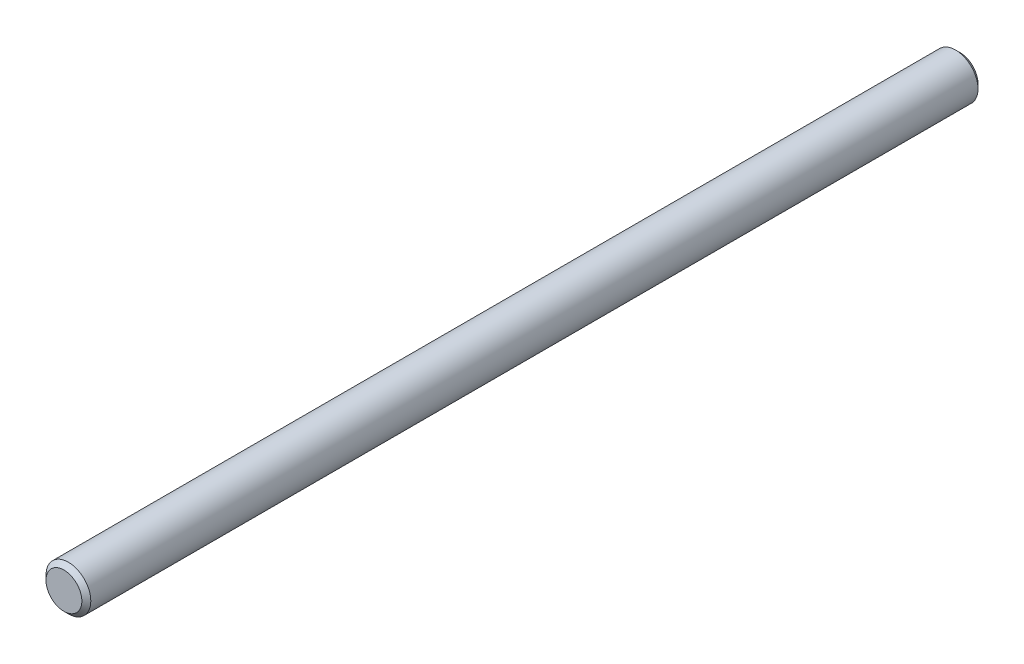
SolidWorks part; units mm, degrees
ref_plane "Front" through (0, 0, 0) normal (0, 0, 1) x (1, 0, 0)
ref_plane "Top" through (0, 0, 0) normal (0, 1, 0) x (1, 0, 0)
ref_plane "Right" through (0, 0, 0) normal (1, 0, 0) x (0, 0, -1)
sketch "Sketch1" plane through (0, 0, 0) normal (0, 0, 1) x (1, 0, 0)
  circle A0 centre (0, 0) radius 3.175
  dimension "dia" = 6.35
sketch "Sketch3" plane through (0, 0, 0) normal (0, 0, 1) x (1, 0, 0)
  circle A0 centre (0, 0) radius 3.175 construction
  circle A1 centre (0, 0) radius 3.175
extrude "Boss-Extrude1" add sketch "Sketch3" along normal mid plane 127
sketch "Sketch2" plane through (0, 0, 0) normal (1, 0, 0) x (0, 0, -1)
  line L0 (63.5, 3.175) -> (-63.5, 3.175) construction
  point P0 (-63.5, 3.175)
  point P1 (63.5, 3.175)
  point P2 (-50.8, 3.175)
  point P3 (50.8, 3.175)
  dimension "D1" = 12.7
  dimension "D2" = 12.7
chamfer "Chamfer1" distance 0.635 angle 45 2 edges at (3.175, 0, 63.5) (3.175, 0, -63.5)
equation "\"D1@Chamfer1\" = \"dia@Sketch1\" / 10"
equation "\"D1@Sketch2\"=\"dia@Sketch1\"*2"
equation "\"D2@Sketch2\"=\"D1@Sketch2\""
